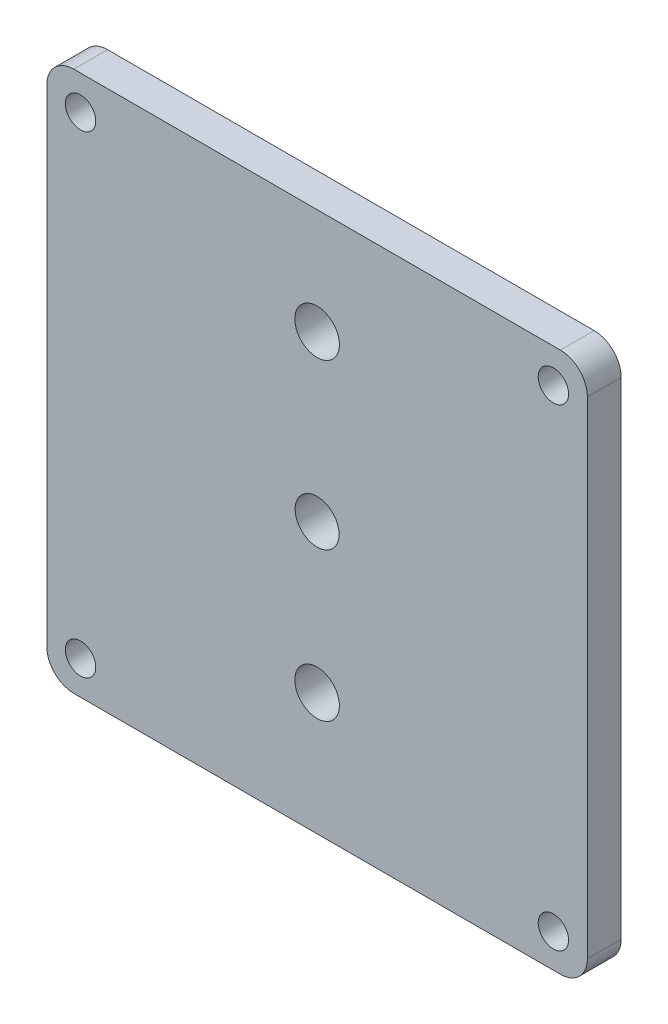
SolidWorks part; units mm, degrees
ref_plane "Plan de face" through (0, 0, 0) normal (0, 0, 1) x (1, 0, 0)
ref_plane "Plan de dessus" through (0, 0, 0) normal (0, 1, 0) x (1, 0, 0)
ref_plane "Plan de droite" through (0, 0, 0) normal (1, 0, 0) x (0, 0, -1)
sketch "Esquisse1" plane through (0, 0, 0) normal (0, 0, 1) x (1, 0, 0)
  line L1 (-36, -40) -> (36, -40)
  line L2 (-40, -36) -> (-40, 36)
  line L3 (-36, 40) -> (36, 40)
  line L4 (40, -36) -> (40, 36)
  line L5 (-40, -40) -> (40, 40) construction
  line L6 (-40, 40) -> (40, -40) construction
  arc A0 (-36, -40) -> (-40, -36) centre (-36, -36) cw
  arc A1 (36, -40) -> (40, -36) centre (36, -36) ccw
  arc A2 (40, 36) -> (36, 40) centre (36, 36) ccw
  arc A3 (-40, 36) -> (-36, 40) centre (-36, 36) cw
  point P0 (0, 0)
  dimension "D3" = 4
  dimension "D1" = 80
  dimension "D2" = 80
extrude "Boss.-Extru.1" add sketch "Esquisse1" along normal blind 5
hole_wizard "Dégagement M41" positions "Esquisse3" profile "Esquisse2" hole size "M4" standard "JIS" end condition through all
sketch "Esquisse3" plane through (0, 0, 5) normal (0, 0, 1) x (1, 0, 0)
  point P0 (-35.0076, 34.9624)
  point P2 (34.9684, 34.9624)
  point P4 (34.9684, -35.0239)
  point P6 (-35.0076, -35.0239)
sketch "Esquisse2" plane through (-35.0076, 34.9624, 5) normal (1, 0, 0) x (0, -1, 0)
  line L0 (0, 0) -> (0, 5)
  line L1 (0, 5) -> (2.25, 5)
  line L2 (2.25, 5) -> (2.25, 0)
  line L5 (2.25, 0) -> (0, 0)
  line L11 (0, -6.35) -> (0, 107.95) construction
  dimension "Diamètre du perçage jusqu'au prochain" = 4.5
  dimension "Profondeur du perçage jusqu'au prochain" = 5
sketch "Esquisse4" plane through (0, 0, 0) normal (0, 0, -1) x (-1, 0, 0)
  circle A0 centre (0, 0) radius 3.25
  dimension "D1" = 6.5
extrude "Enlèv. mat.-Extru.1" cut sketch "Esquisse4" against normal through all
hole_wizard "Dégagement M61" positions "Esquisse6" profile "Esquisse5" hole size "M6" standard "JIS" end condition through all
sketch "Esquisse6" plane through (0, 0, 0) normal (0, 0, -1) x (-1, 0, 0)
  point P0 (0, -21.9164)
  point P2 (0, 24.3464)
sketch "Esquisse5" plane through (0, -21.9164, 0) normal (1, 0, 0) x (0, 1, 0)
  line L0 (0, 0) -> (0, 5)
  line L1 (0, 5) -> (3.3, 5)
  line L2 (3.3, 5) -> (3.3, 0)
  line L5 (3.3, 0) -> (0, 0)
  line L11 (0, -6.35) -> (0, 107.95) construction
  dimension "Diamètre du perçage jusqu'au prochain" = 6.6
  dimension "Profondeur du perçage jusqu'au prochain" = 5
